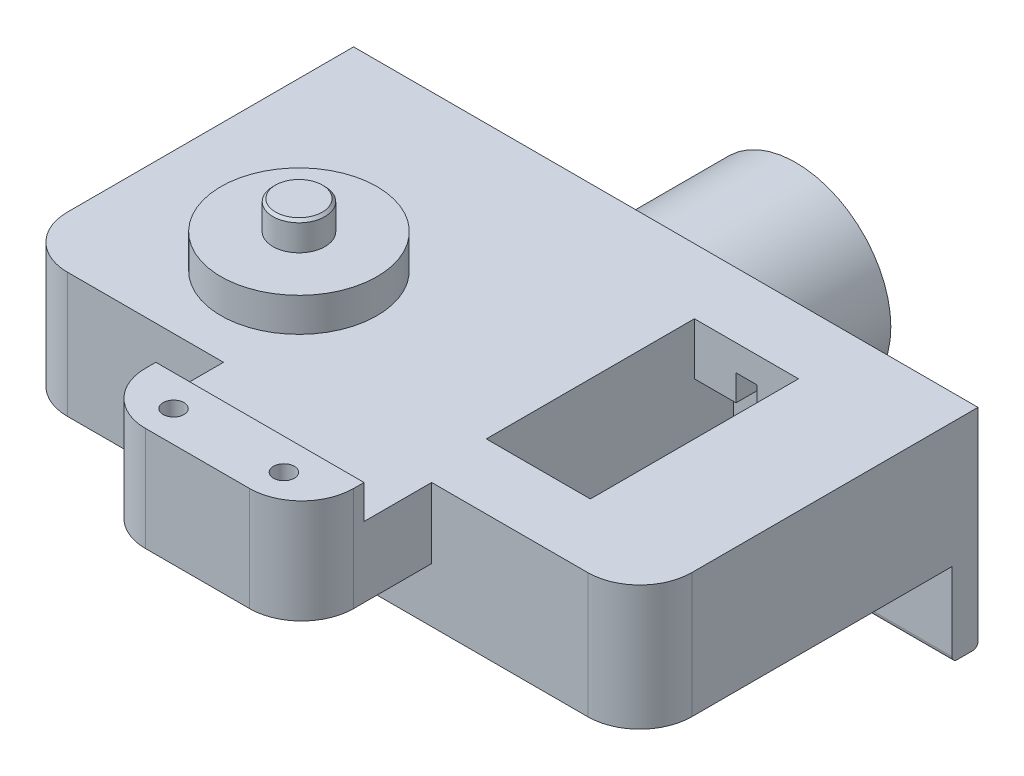
SolidWorks part; units mm, degrees
ref_plane "前视基准面" through (0, 0, 0) normal (0, 0, 1) x (1, 0, 0)
ref_plane "上视基准面" through (0, 0, 0) normal (0, 1, 0) x (1, 0, 0)
ref_plane "右视基准面" through (0, 0, 0) normal (1, 0, 0) x (0, 0, -1)
other "Configuration Table"
sketch "草图1" plane through (0, 0, 0) normal (0, 0, 1) x (1, 0, 0)
  circle A0 centre (0, 0) radius 18.25
  dimension "D1" = 36.5
extrude "凸台-拉伸1" add sketch "草图1" along normal blind 25
sketch "草图2" plane through (0, 0, 25) normal (0, 0, 1) x (1, 0, 0)
  circle A0 centre (0, 0) radius 12.5
  dimension "D1" = 25
extrude "切除-拉伸1" cut sketch "草图2" against normal blind 25
sketch "草图3" plane through (0, 0, 25) normal (0, 0, 1) x (1, 0, 0)
  line L1 (-60, 20) -> (60, 20)
  line L2 (-60, 20) -> (-60, -20)
  line L3 (-60, -20) -> (60, -20)
  line L4 (60, 20) -> (60, -20)
  dimension "D1" = 120
  dimension "D2" = 40
  dimension "D3" = 20
  dimension "D4" = 60
extrude "凸台-拉伸2" add sketch "草图3" along normal blind 65
sketch "草图5" plane through (0, -20, 0) normal (0, -1, 0) x (1, 0, 0)
  line L0 (-60, 25) -> (60, 25) construction
  line L1 (18, 85) -> (38, 85)
  line L2 (18, 85) -> (18, 30)
  line L3 (18, 30) -> (38, 30)
  line L4 (38, 85) -> (38, 30)
  line L5 (60, 90) -> (60, 25) construction
  dimension "D1" = 55
  dimension "D2" = 20
  dimension "D3" = 5
  dimension "D4" = 22
extrude "切除-拉伸2" cut sketch "草图5" against normal blind 30
sketch "草图6" plane through (0, 10, 0) normal (0, -1, 0) x (1, 0, 0)
  line L0 (18, 85) -> (18, 30) construction
  line L1 (18, 77.5) -> (38, 77.5)
  line L2 (18, 77.5) -> (18, 37.5)
  line L3 (18, 37.5) -> (38, 37.5)
  line L4 (38, 77.5) -> (38, 37.5)
  line L5 (38, 30) -> (38, 85) construction
  line L6 (38, 85) -> (18, 85) construction
  dimension "D1" = 40
  dimension "D2" = 7.5
extrude "切除-拉伸3" cut sketch "草图6" against normal blind 30
sketch "草图7" plane through (0, 10, 0) normal (0, -1, 0) x (1, 0, 0)
  line L0 (38, 85) -> (18, 85) construction
  line L1 (26, 85) -> (30, 85)
  line L2 (26, 85) -> (26, 30)
  line L3 (26, 30) -> (30, 30)
  line L4 (30, 85) -> (30, 30)
  line L5 (18, 30) -> (38, 30) construction
  line L6 (38, 30) -> (38, 85) construction
  dimension "D1" = 4
  dimension "D2" = 8
extrude "切除-拉伸4" cut sketch "草图7" against normal blind 5
sketch "草图8" plane through (0, 20, 0) normal (0, 1, 0) x (1, 0, 0)
  line L0 (-60, -90) -> (-60, -25) construction
  line L3 (38, -77.5) -> (18, -77.5) construction
  circle A0 centre (-28, -67.5) radius 5
  dimension "D1" = 10
  dimension "D2" = 32
  dimension "D3" = 10
extrude "凸台-拉伸4" add sketch "草图8" along normal blind 12
sketch "草图9" plane through (0, 0, 90) normal (0, 0, 1) x (1, 0, 0)
  line L0 (-60, 20) -> (-60, -20) construction
  line L1 (-60, -4) -> (60, -4)
  line L2 (-60, -4) -> (-60, -20)
  line L3 (-60, -20) -> (60, -20)
  line L4 (60, -4) -> (60, -20)
  dimension "D1" = 16
extrude "切除-拉伸5" cut sketch "草图9" against normal blind 60 and the other way through all
sketch "草图10" plane through (0, 20, 0) normal (0, 1, 0) x (1, 0, 0)
  line L0 (60, -90) -> (-60, -90) construction
  line L1 (-20, -90) -> (20, -90)
  line L2 (-20, -90) -> (-20, -115)
  line L3 (-20, -115) -> (20, -115)
  line L4 (20, -90) -> (20, -115)
  line L5 (60, -90) -> (60, -25) construction
  dimension "D1" = 40
  dimension "D2" = 40
  dimension "D3" = 25
extrude "凸台-拉伸5" add sketch "草图10" against normal blind 13.5
sketch "草图13" plane through (0, 20, 0) normal (0, 1, 0) x (1, 0, 0)
  line L2 (-20, -115) -> (20, -115) construction
  line L3 (0, -115) -> (0, -50115) construction
  circle A1 centre (-10.6003, -109) radius 2
  circle A2 centre (-28, -67.5) radius 5 construction
  circle A3 centre (10.6003, -109) radius 2
  point P4 (0, -115)
  dimension "D1" = 4
  dimension "D4" = 45
  dimension "D5" = 6
extrude "切除-拉伸6" cut sketch "草图13" against normal blind 30
sketch "草图14" plane through (0, 20, 0) normal (0, 1, 0) x (1, 0, 0)
  circle A0 centre (-28, -67.5) radius 15
  dimension "D1" = 30
extrude "凸台-拉伸6" add sketch "草图14" along normal blind 6.5
sketch "草图15" plane through (0, 20, 0) normal (0, 1, 0) x (1, 0, 0)
  line L0 (-20, -90) -> (-20, -115) construction
  line L1 (-20, -103) -> (20, -103)
  line L2 (-20, -103) -> (-20, -115)
  line L3 (-20, -115) -> (20, -115)
  line L4 (20, -103) -> (20, -115)
  circle A2 centre (-10.6003, -109) radius 2 construction
  circle A3 centre (-10.6003, -109) radius 2
  circle A4 centre (10.6003, -109) radius 2 construction
  circle A5 centre (10.6003, -109) radius 2
  dimension "D1" = 12
extrude "凸台-拉伸7" add sketch "草图15" along normal blind 6.5
fillet "圆角1" radius 10 2 edges at (-20, 16.5, 115) (20, 16.5, 115)
fillet "圆角2" radius 10 2 edges at (-60, 8, 90) (60, 8, 90)
fillet "圆角3" radius 1 2 edges at (0, -20, 25) (0, -20, 30)
chamfer "倒角1" distance 0.5 angle 45 1 edges at (-28, 32, 72.5)
